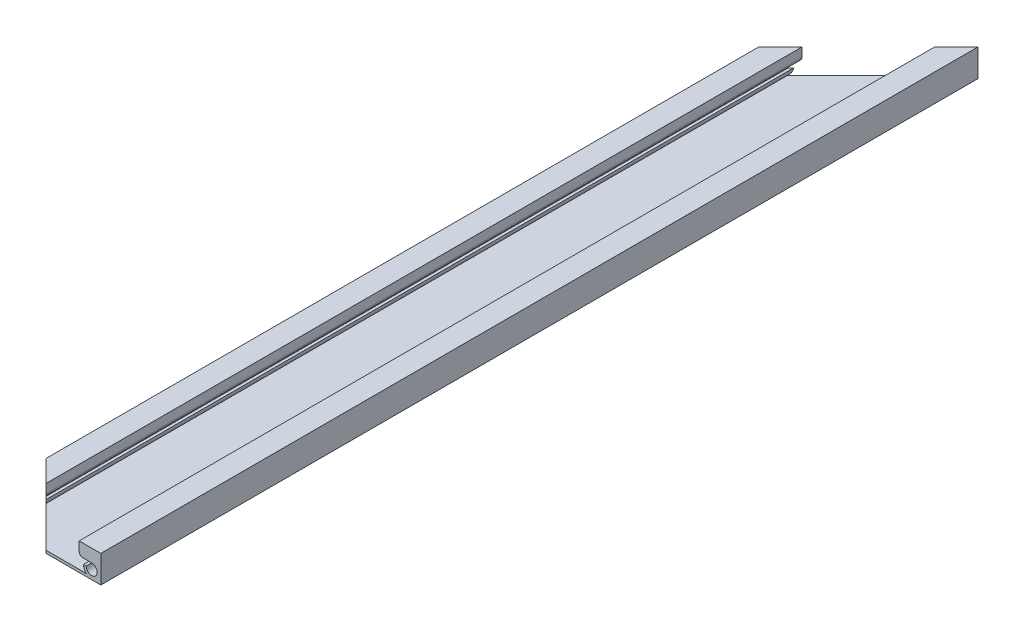
SolidWorks part; units mm, degrees
ref_plane "정면" through (0, 0, 0) normal (0, 0, 1) x (1, 0, 0)
ref_plane "윗면" through (0, 0, 0) normal (0, 1, 0) x (1, 0, 0)
ref_plane "우측면" through (0, 0, 0) normal (1, 0, 0) x (0, 0, -1)
sketch "스케치1" plane through (0, 0, 0) normal (0, 0, 1) x (1, 0, 0)
  line L1 (-30, 7.5) -> (30, 7.5)
  line L2 (-30, 7.5) -> (-30, -7.5)
  line L3 (-30, -7.5) -> (30, -7.5)
  line L4 (30, 7.5) -> (30, -7.5)
  line L5 (-30, 7.5) -> (30, -7.5) construction
  line L6 (-30, -7.5) -> (30, 7.5) construction
  point P0 (0, 0)
  dimension "D1" = 60
  dimension "D2" = 15
extrude "보스-돌출1" add sketch "스케치1" along normal blind 510
sketch "스케치2" plane through (0, 0, 0) normal (0, 0, -1) x (-1, 0, 0)
  line L0 (30, -7.5) -> (-30, -7.5) construction
  line L2 (-30, -7.5) -> (-30, 7.5) construction
  line L3 (30, 7.5) -> (30, -7.5) construction
  circle A0 centre (-25, -2.5) radius 3
  circle A1 centre (25, -2.5) radius 3
  dimension "D1" = 6
  dimension "D3" = 5
  dimension "D4" = 6
  dimension "D6" = 5
  dimension "D2" = 5
  dimension "D5" = 5
extrude "컷-돌출1" cut sketch "스케치2" against normal through all
sketch "스케치3" plane through (0, 0, 0) normal (0, 0, -1) x (-1, 0, 0)
  line L0 (-22.1716, -6) -> (22.1716, -6)
  line L1 (-20.5, -2.5) -> (-25, -2.5)
  line L2 (-25, -2.5) -> (-25, 0.5)
  line L3 (-25, 0.5) -> (25, 0.5)
  line L4 (25, 0.5) -> (25, -2.5)
  line L5 (25, -2.5) -> (20.5, -2.5)
  line L6 (30, -7.5) -> (-30, -7.5) construction
  arc A0 (22.1716, -6) -> (20.5, -2.5) centre (25, -2.5) cw
  arc A1 (-22.1716, -6) -> (-20.5, -2.5) centre (-25, -2.5) ccw
  circle A2 centre (-25, -2.5) radius 3 construction
  circle A3 centre (25, -2.5) radius 3 construction
  dimension "D2" = 1.5
  dimension "D1" = 1.5
  dimension "1.5" = 1.5
extrude "컷-돌출2" cut sketch "스케치3" against normal through all
sketch "스케치4" plane through (0, 0, 0) normal (0, 0, -1) x (-1, 0, 0)
  line L0 (-18.1431, 0.5) -> (18.1569, 0.5)
  line L1 (25, 0.5) -> (-25, 0.5) construction
  line L2 (-18.1431, 0.5) -> (-18.1431, 7.5)
  line L3 (-30, 7.5) -> (30, 7.5) construction
  line L4 (-18.1431, 7.5) -> (18.1569, 7.5)
  line L5 (18.1569, 7.5) -> (18.1569, 0.5)
  point P5 (0, 0)
  dimension "D1" = 36.3
extrude "컷-돌출3" cut sketch "스케치4" against normal through all
fillet "필렛1" radius 2 2 edges at (-18.1569, 0.5, 255) (18.1431, 0.5, 255)
sketch "스케치5" plane through (0, -7.5, 0) normal (0, -1, 0) x (1, 0, 0)
  line L0 (-30, 510) -> (-30, 450)
  line L1 (-30, 510) -> (-30, 0) construction
  line L2 (-30, 450) -> (30, 510)
  line L5 (-30, 0) -> (30, 0)
  line L6 (-30, 255) -> (30, 255) construction
  line L7 (30, 510) -> (30, 0) construction
  line L15 (-30, 510) -> (30, 510)
  line L17 (-30, 60) -> (30, 0)
  line L18 (-30, 0) -> (-30, 60)
  dimension "D1" = 45
extrude "컷-돌출4" cut sketch "스케치5" against normal through all
sketch "스케치7" plane through (0, -7.5, 0) normal (0, -1, 0) x (1, 0, 0)
  line L0 (-30, 450) -> (30, 510) construction
  line L5 (30, 510) -> (0, 510)
  line L6 (30, 510) -> (30, 480)
  line L7 (30, 480) -> (0, 480)
  line L8 (0, 510) -> (0, 480)
extrude "컷-돌출6" cut sketch "스케치7" against normal through all and the other way through all
